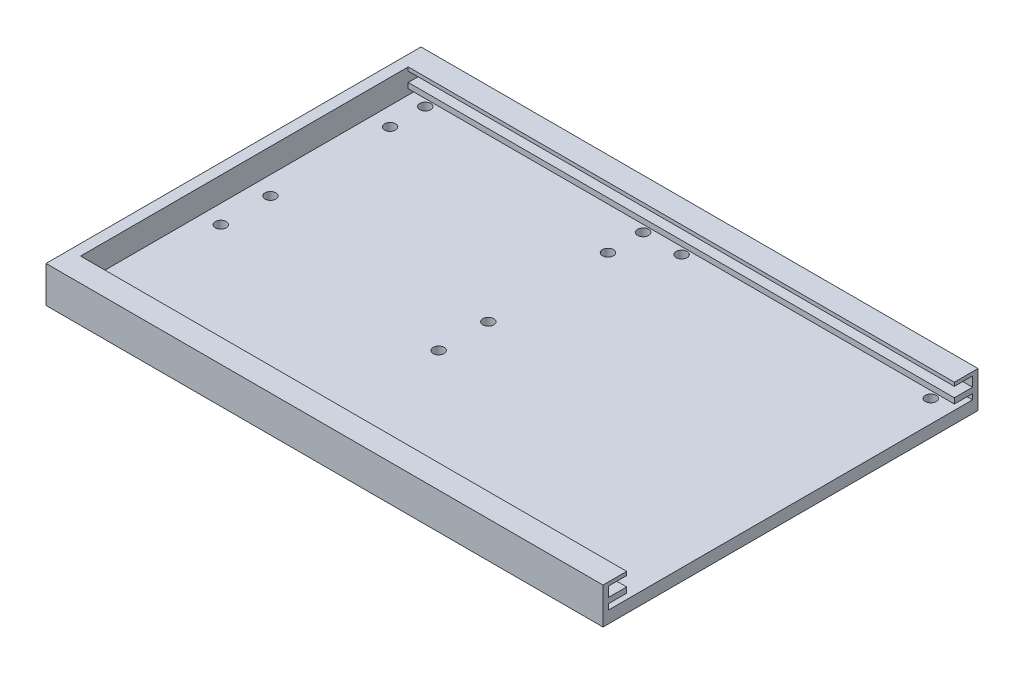
SolidWorks part; units mm, degrees
ref_plane "前视基准面" through (0, 0, 0) normal (0, 0, 1) x (1, 0, 0)
ref_plane "上视基准面" through (0, 0, 0) normal (0, 1, 0) x (1, 0, 0)
ref_plane "右视基准面" through (0, 0, 0) normal (1, 0, 0) x (0, 0, -1)
sketch "草图1" plane through (0, 0, 0) normal (1, 0, 0) x (0, 0, -1)
  line L1 (-51.5, 5) -> (51.5, 5)
  line L2 (-51.5, 5) -> (-51.5, -5)
  line L3 (-51.5, -5) -> (51.5, -5)
  line L4 (51.5, 5) -> (51.5, -5)
  line L5 (-51.5, 5) -> (51.5, -5) construction
  line L6 (-51.5, -5) -> (51.5, 5) construction
  point P0 (0, 0)
  dimension "D1" = 10
  dimension "D2" = 103
extrude "凸台-拉伸1" add sketch "草图1" along normal blind 153
sketch "草图2" plane through (153, 0, 0) normal (1, 0, 0) x (0, 0, -1)
  line L0 (0, 20.2221) -> (0, -20.8727) construction
  line L1 (0, 5) -> (-45, 5)
  line L2 (51.5, 5) -> (-51.5, 5) construction
  line L3 (-45, 5) -> (-45, 4)
  line L4 (-45, 4) -> (45, 4)
  line L5 (45, 4) -> (45, 5)
  line L6 (45, 5) -> (0, 5)
  dimension "D1" = 45
  dimension "D2" = 45
  dimension "D3" = 1
extrude "切除-拉伸1" cut sketch "草图2" against normal blind 150
sketch "草图3" plane through (153, 0, 0) normal (1, 0, 0) x (0, 0, -1)
  line L0 (0, 10.2066) -> (0, -10.1786) construction
  line L1 (0, 4) -> (-50, 4)
  line L2 (-45, 4) -> (45, 4) construction
  line L3 (-50, 4) -> (-50, 1.3)
  line L4 (-50, 1.3) -> (50, 1.3)
  line L5 (50, 1.3) -> (50, 4)
  line L6 (50, 4) -> (0, 4)
  dimension "D1" = 50
  dimension "D2" = 50
  dimension "D3" = 2.7
extrude "切除-拉伸2" cut sketch "草图3" against normal blind 150
sketch "草图4" plane through (153, 0, 0) normal (1, 0, 0) x (0, 0, -1)
  line L0 (0, 9.6601) -> (0, -6.777) construction
  line L1 (0, 1.3) -> (-45, 1.3)
  line L2 (-50, 1.3) -> (50, 1.3) construction
  line L3 (-45, 1.3) -> (-45, -0.2)
  line L4 (-45, -0.2) -> (45, -0.2)
  line L5 (45, -0.2) -> (45, 1.3)
  line L6 (45, 1.3) -> (0, 1.3)
  dimension "D1" = 45
  dimension "D2" = 45
  dimension "D3" = 1.5
extrude "切除-拉伸3" cut sketch "草图4" against normal blind 150
sketch "草图5" plane through (153, 0, 0) normal (1, 0, 0) x (0, 0, -1)
  line L0 (0, 8.8039) -> (0, -11.0655) construction
  line L1 (0, -0.2) -> (-50, -0.2)
  line L2 (-45, -0.2) -> (45, -0.2) construction
  line L3 (-50, -0.2) -> (-50, -1.7)
  line L4 (-50, -1.7) -> (50, -1.7)
  line L5 (50, -1.7) -> (50, -0.2)
  line L6 (50, -0.2) -> (0, -0.2)
  dimension "D1" = 50
  dimension "D2" = 50
  dimension "D3" = 1.5
extrude "切除-拉伸4" cut sketch "草图5" against normal blind 150
sketch "草图6" plane through (0, -5, 0) normal (0, -1, 0) x (1, 0, 0)
  line L0 (-4.4743, 0) -> (165.3436, 0) construction
  line L1 (150, 47.55) -> (150, -47.55)
  line L2 (150, 47.55) -> (75.4, 47.55)
  line L3 (75.4, 47.55) -> (75.4, -47.55)
  line L4 (75.4, -47.55) -> (150, -47.55)
  line L5 (153, 51.5) -> (153, -51.5) construction
  line L6 (112.7, 56.8802) -> (112.7, -57.0546) construction
  line L7 (67.9014, 0) -> (160.0987, 0) construction
  line L9 (78.475, 44.4278) -> (146.925, 44.4278)
  line L10 (78.475, 44.4278) -> (78.475, -44.6022)
  line L11 (78.475, -44.6022) -> (146.925, -44.6022)
  line L12 (146.925, 44.4278) -> (146.925, -44.6022)
  line L13 (78.475, 44.4278) -> (146.925, -44.6022) construction
  line L14 (78.475, -44.6022) -> (146.925, 44.4278) construction
  circle A0 centre (146.925, 44.4278) radius 1.5
  circle A1 centre (78.475, 44.4278) radius 1.5
  circle A2 centre (78.475, -44.6022) radius 1.5
  circle A3 centre (146.925, -44.6022) radius 1.5
  point P13 (112.7, -0.0872)
  dimension "D8" = 3
  dimension "D9" = 3
  dimension "D10" = 3
  dimension "D11" = 3
  dimension "D1" = 47.55
  dimension "D2" = 47.55
  dimension "D3" = 74.6
  dimension "D4" = 3
  dimension "D5" = 112.7
  dimension "D6" = 68.45
  dimension "D7" = 89.03
extrude "切除-拉伸6" cut sketch "草图6" against normal blind 4 contours L9 A1 L10 | L10 A1 L9 | L12 A0 L9 | L9 A0 L12 | L10 A2 L11 | L11 A2 L10 | L11 A3 L12 | L12 A3 L11
sketch "草图7" plane through (0, -5, 0) normal (0, -1, 0) x (1, 0, 0)
  line L0 (-21.3718, 0) -> (112.5, 0) construction
  line L1 (78.475, 44.4278) -> (-17.516, 44.4278) construction
  line L4 (8.075, 44.425) -> (67.925, 44.425)
  line L5 (8.075, 44.425) -> (8.075, 11.575)
  line L6 (8.075, 11.575) -> (67.925, 11.575)
  line L7 (67.925, 44.425) -> (67.925, 11.575)
  line L8 (8.075, 44.425) -> (67.925, 11.575) construction
  line L9 (8.075, 11.575) -> (67.925, 44.425) construction
  line L10 (0, 51.5) -> (0, -51.5) construction
  line L11 (8.075, -2.075) -> (67.925, -2.075)
  line L12 (8.075, -2.075) -> (8.075, -34.925)
  line L13 (8.075, -34.925) -> (67.925, -34.925)
  line L14 (67.925, -2.075) -> (67.925, -34.925)
  line L15 (8.075, -2.075) -> (67.925, -34.925) construction
  line L16 (8.075, -34.925) -> (67.925, -2.075) construction
  line L18 (153, -51.5) -> (0, -51.5) construction
  line L19 (78.475, -44.6022) -> (-14.2326, -44.6022) construction
  line L20 (67.925, -34.925) -> (67.925, -52.534) construction
  line L21 (8.075, -34.925) -> (8.075, -50.4155) construction
  circle A0 centre (67.925, 44.425) radius 1.5
  circle A1 centre (8.075, 44.425) radius 1.5
  circle A2 centre (8.075, 11.575) radius 1.5
  circle A3 centre (67.925, 11.575) radius 1.5
  circle A4 centre (8.075, -2.075) radius 1.5
  circle A5 centre (67.925, -2.075) radius 1.5
  circle A6 centre (67.925, -34.925) radius 1.5
  circle A7 centre (8.075, -34.925) radius 1.5
  circle A8 centre (67.925, -44.6022) radius 1.5
  circle A9 centre (8.075, -44.6022) radius 1.5
  point P6 (38, 28)
  point P8 (38, 28)
  point P14 (38, -18.5)
  point P16 (38, -18.5)
  dimension "D5" = 3
  dimension "D6" = 3
  dimension "D7" = 3
  dimension "D8" = 3
  dimension "D11" = 3
  dimension "D12" = 3
  dimension "D13" = 3
  dimension "D14" = 3
  dimension "D15" = 3
  dimension "D16" = 3
  dimension "D1" = 28
  dimension "D2" = 32.85
  dimension "D3" = 59.85
  dimension "D4" = 38
  dimension "D9" = 38
  dimension "D10" = 33
extrude "切除-拉伸7" cut sketch "草图7" against normal blind 4 contours L5 A1 L4 | L4 A1 L5 | L7 A0 L4 | L4 A0 L7 | L11 A4 L12 | L12 A4 L11 | L14 A5 L11 | L11 A5 L14 | L6 A3 L7 | L7 A3 L6 | L5 A2 L6 | L6 A2 L5 | L13 A7 L12 | L12 A7 L13 | L13 A6 L14 | L14 A6 L13 | A8 | A9
